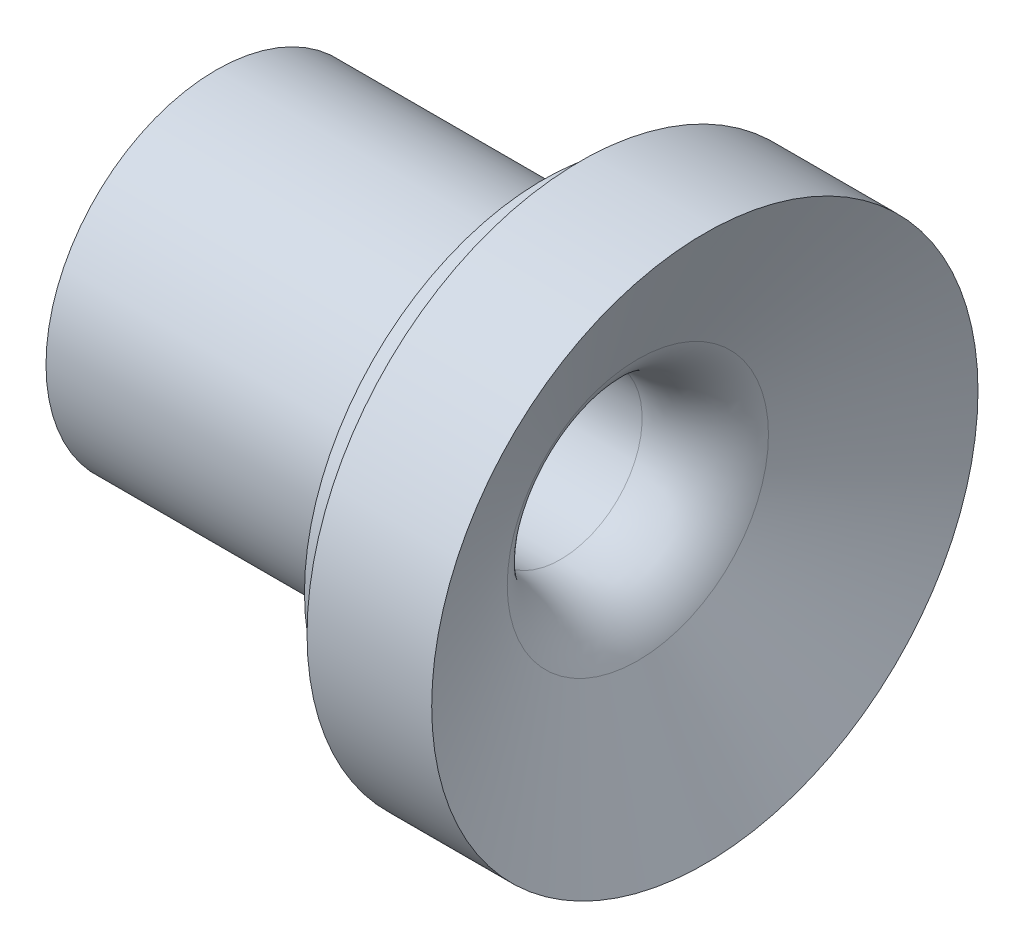
SolidWorks part; units mm, degrees
material "C (Graphite)"
ref_plane "Plan de face" through (0, 0, 0) normal (0, 0, 1) x (1, 0, 0)
ref_plane "Plan de dessus" through (0, 0, 0) normal (0, 1, 0) x (1, 0, 0)
ref_plane "Plan de droite" through (0, 0, 0) normal (1, 0, 0) x (0, 0, -1)
sketch "Esquisse1" plane through (0, 0, 0) normal (0, 0, 1) x (1, 0, 0)
  line L0 (1.9817, 8.978) -> (7.8235, 8.978)
  line L1 (7.8235, 8.978) -> (4.6838, 2.2984)
  line L3 (-5.0365, 0) -> (-15.0765, 1.816)
  line L4 (-15.0765, 1.816) -> (-15.0765, 4.152)
  line L5 (-15.0765, 4.152) -> (-2.0005, 4.152)
  line L6 (-1.3577, 4.3859) -> (-0.1282, 5.4177)
  line L7 (0.2291, 6.1837) -> (0.2291, 7.346)
  line L8 (0.2291, 7.346) -> (1.9817, 7.346)
  line L9 (1.9817, 7.346) -> (1.9817, 8.978)
  line L10 (-19.4769, -3.822) -> (13.1452, -3.822) construction
  line L11 (-5.0365, 0) -> (0.8035, 0)
  line L12 (0.8035, 0) -> (1.0638, 0)
  arc A0 (4.6838, 2.2984) -> (1.0638, 0) centre (1.0638, 4) cw
  arc A1 (-2.0005, 4.152) -> (-1.3577, 4.3859) centre (-2.0005, 5.152) ccw
  arc A2 (-0.1282, 5.4177) -> (0.2291, 6.1837) centre (-0.7709, 6.1837) ccw
  point P17 (3.6035, 0)
  point P20 (-1.6365, 4.152)
  point P23 (0.2291, 5.7174)
  dimension "D13" = 4
  dimension "D14" = 1
  dimension "D1" = 5.8418
  dimension "D2" = 7.974
  dimension "D3" = 13.44
  dimension "D4" = 7.5944
  dimension "D5" = 11.168
  dimension "D6" = 2.336
  dimension "D7" = 22.9
  dimension "D8" = 10.04
  dimension "D9" = 5.84
  dimension "D11" = 12.8
  dimension "D12" = 2.8
revolve "Révolution1" add sketch "Esquisse1" angle 360 about L10
scale "Scale1" scale about centroid uniform scaling yes scale factor 1.706037
